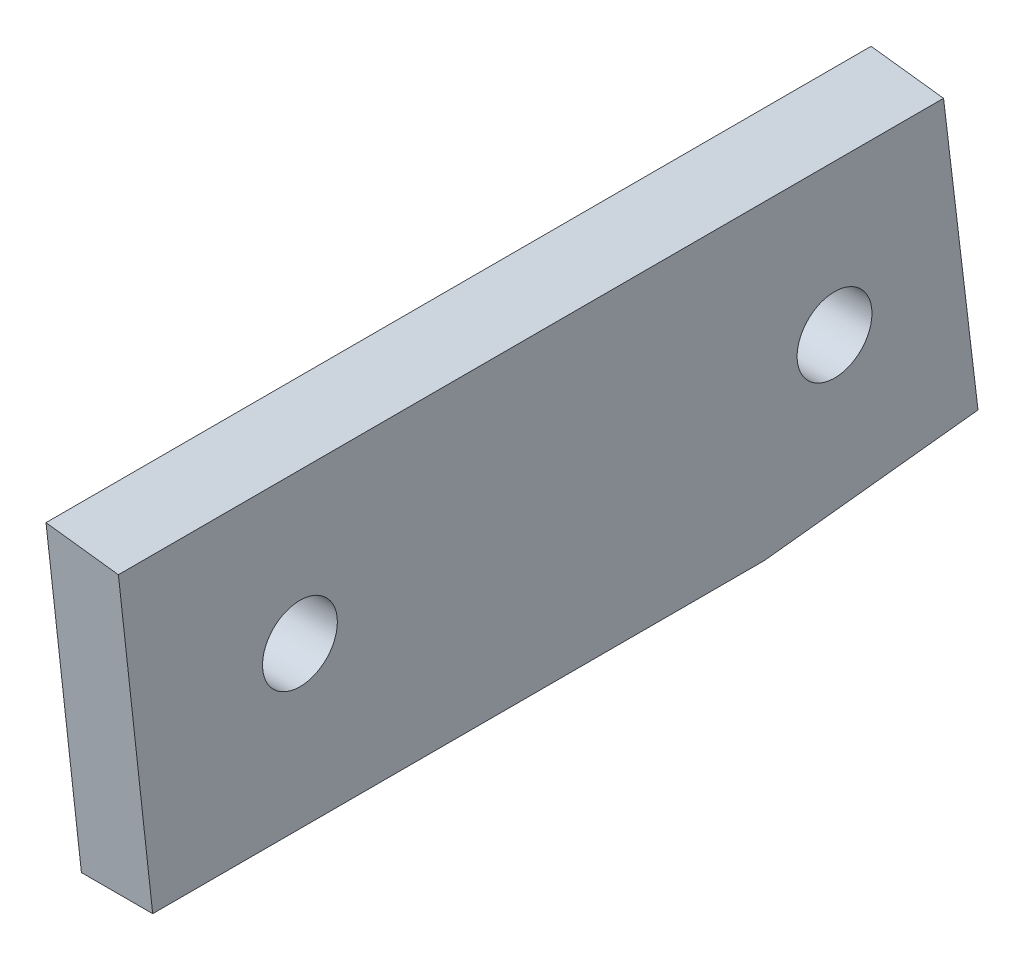
SolidWorks part; units mm, degrees
ref_plane "Frontal" through (0, 0, 0) normal (0, 0, 1) x (1, 0, 0)
ref_plane "Horizontal" through (0, 0, 0) normal (0, 1, 0) x (1, 0, 0)
ref_plane "Vertical" through (0, 0, 0) normal (1, 0, 0) x (0, 0, -1)
sketch "Esquisse1" plane through (0, 0, 0) normal (0, 0, 1) x (1, 0, 0)
  line L0 (0, 0) -> (4, 0)
  line L1 (4, 0) -> (4, 17.4378)
  line L2 (0, 0) -> (0, 18)
  line L3 (0, 18) -> (4, 17.4378)
  line L4 (0, 18) -> (66.3935, 18) construction
  dimension "D1" = 18
  dimension "D2" = 4
  dimension "D3" = 8
extrude "Extrusion1" add sketch "Esquisse1" along normal blind 48.3
hole_wizard "Trou taraudé M51" positions "Esquisse3" profile "Esquisse2" tap size "M5" standard "ISO" end condition through all
sketch "Esquisse3" plane through (4, 0, 0) normal (1, 0, 0) x (0, 0, -1)
  line L0 (4.5763, 9) -> (-32.6286, 9) construction
  line L2 (-48.3, 0) -> (0, 0) construction
  line L3 (-48.3, 0) -> (-48.3, 17.4378) construction
  point P0 (-8.05, 9)
  point P4 (-38.05, 9)
  dimension "D1" = 10.25
  dimension "D2" = 30
  dimension "D3" = 9
sketch "Esquisse2" plane through (4, 9, 8.05) normal (0, 1, 0) x (0, 0, -1)
  line L0 (0, 0) -> (0, 4)
  line L1 (0, 4) -> (2.1, 4)
  line L2 (2.1, 4) -> (2.1, 0)
  line L5 (2.1, 0) -> (0, 0)
  line L11 (0, -6.35) -> (0, 107.95) construction
  dimension "Diamètre du trou pour taraudage jusqu'au prochain" = 4.2
  dimension "Profondeur du trou pour taraudage jusqu'au prochain" = 4
cosmetic thread "Filetage de perçage1" parameters "D2"=5
cosmetic thread "Filetage de perçage2" parameters "D2"=5
sketch "Esquisse4" plane through (0, 0, 0) normal (-1, 0, 0) x (0, 0, 1)
  line L0 (48.3, 18) -> (46.3128, 0)
  line L2 (0, 0) -> (0, 1.3248)
  line L3 (48.3, 0) -> (48.3, 18)
  line L4 (0, 1.3248) -> (12, 0)
  line L12 (48.3, 0) -> (46.3128, 0)
  line L14 (12, 0) -> (0, 0)
  line L15 (48.3, 0) -> (0, 0) construction
  line L16 (48.3, 0) -> (0, 0) construction
  dimension "D1" = 6.3
  dimension "D2" = 6.3
  dimension "D3" = 36.3
extrude "Extrusion2" cut sketch "Esquisse4" against normal through all
sketch "Esquisse5" plane through (0, 0, 0) normal (-1, 0, 0) x (0, 0, 1)
  line L0 (0, 1.3248) -> (2, 18)
  line L1 (48.3, 18) -> (0, 18) construction
  line L2 (2, 18) -> (0, 18)
  line L3 (0, 18) -> (0, 1.3248)
  dimension "D1" = 46.3
extrude "Extrusion3" cut sketch "Esquisse5" against normal through all
